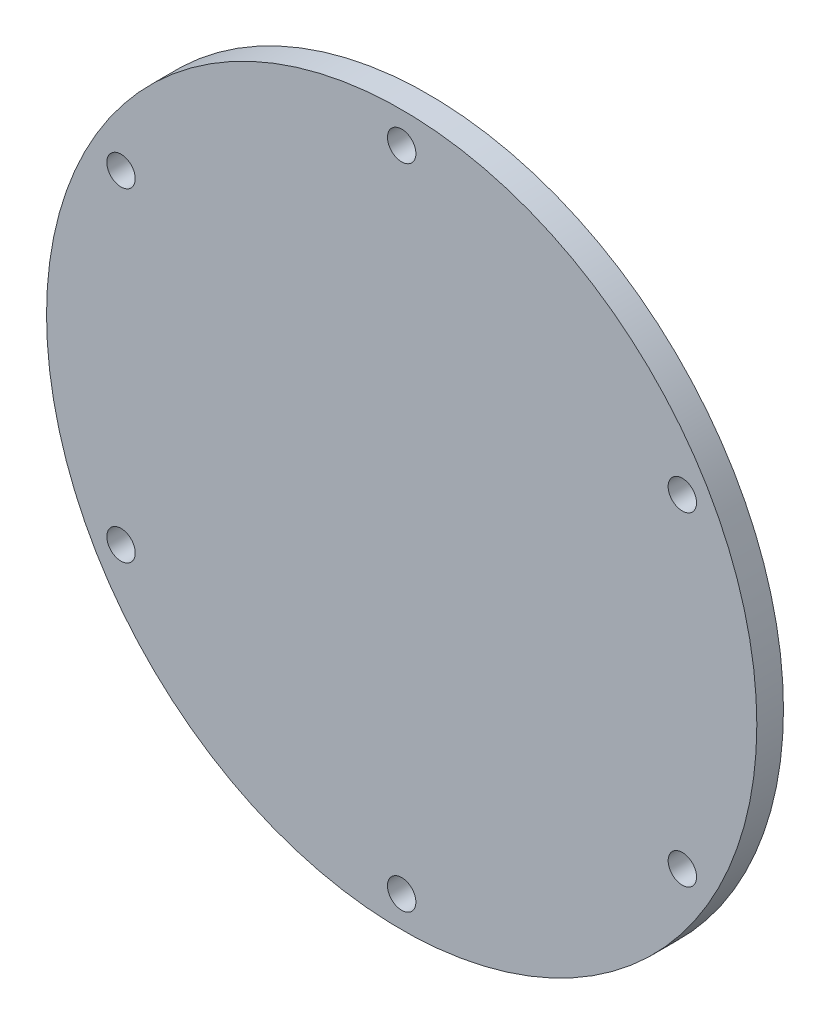
SolidWorks part; units mm, degrees
ref_plane "Front Plane" through (0, 0, 0) normal (0, 0, 1) x (1, 0, 0)
ref_plane "Top Plane" through (0, 0, 0) normal (0, 1, 0) x (1, 0, 0)
ref_plane "Right Plane" through (0, 0, 0) normal (1, 0, 0) x (0, 0, -1)
sketch "Sketch1" plane through (0, 0, 0) normal (0, 0, 1) x (1, 0, 0)
  circle A0 centre (0, 0) radius 40 construction
  circle A1 centre (0, 0) radius 40
  circle A2 centre (31.6099, -18.25) radius 1.6
  circle A3 centre (31.6099, 18.25) radius 1.6
  circle A4 centre (0, 36.5) radius 1.6
  circle A5 centre (-31.6099, 18.25) radius 1.6
  circle A6 centre (-31.6099, -18.25) radius 1.6
  circle A7 centre (0, -36.5) radius 1.6
  point P3 (31.6099, -18.25)
  point P4 (31.6099, 18.25)
  point P6 (0, -36.5)
  point P8 (-31.6099, -18.25)
  point P10 (-31.6099, 18.25)
  point P12 (0, 36.5)
  dimension "D1" = 3.2
  dimension "D2" = 3.2
  dimension "D3" = 3.2
  dimension "D4" = 3.2
  dimension "D5" = 3.2
  dimension "D6" = 3.2
extrude "Boss-Extrude1" add sketch "Sketch1" along normal blind 3
